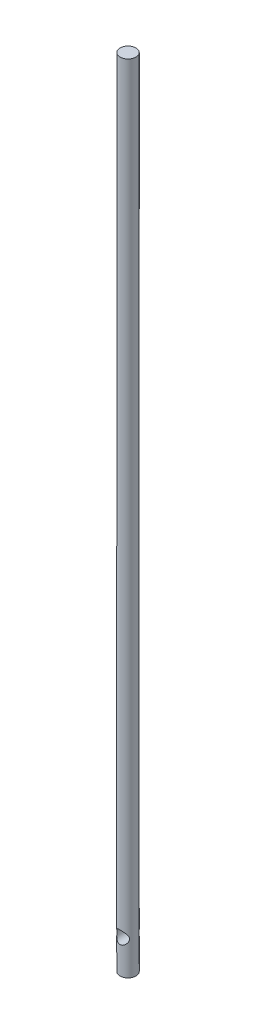
SolidWorks part; units mm, degrees
material "灰铸铁 (SN)"
ref_plane "前视基准面" through (0, 0, 0) normal (0, 0, 1) x (1, 0, 0)
ref_plane "上视基准面" through (0, 0, 0) normal (0, 1, 0) x (1, 0, 0)
ref_plane "右视基准面" through (0, 0, 0) normal (1, 0, 0) x (0, 0, -1)
sketch "草图1" plane through (0, 0, 0) normal (0, 1, 0) x (1, 0, 0)
  circle A0 centre (0, 0) radius 1.5
extrude "凸台-拉伸1" add sketch "草图1" along normal blind 150
sketch "草图3" plane through (0, 0, 0) normal (0, 0, 1) x (1, 0, 0)
  circle A0 centre (0, 6.3386) radius 1.2
  dimension "D1" = 2.4
extrude "切除-拉伸2" cut sketch "草图3" against normal mid plane 300
sketch "草图5" plane through (0, 0, 0) normal (0, 0, 1) x (1, 0, 0)
  line L0 (0, 123.9855) -> (0, 10.9306) construction
  line L1 (1.2, 123.9855) -> (1.2, 10.9306)
  line L2 (-1.2, 123.9855) -> (-1.2, 10.9306)
  arc A0 (1.2, 123.9855) -> (-1.2, 123.9855) centre (0, 123.9855) ccw
  arc A1 (-1.2, 10.9306) -> (1.2, 10.9306) centre (0, 10.9306) ccw
  point P3 (0, 67.458)
  dimension "D1" = 2.4
extrude "切除-拉伸3" cut sketch "草图5" against normal blind 10
sketch "草图9" plane through (0, 0, 0) normal (0, 0, -1) x (-1, 0, 0)
  line L0 (0, 9.7306) -> (0, 125.1855)
  arc A0 (-1.2, 10.9306) -> (1.2, 10.9306) centre (0, 10.9306) ccw construction
  arc A1 (1.2, 123.9855) -> (-1.2, 123.9855) centre (0, 123.9855) ccw construction
sketch "草图10" plane through (0, 0, 0) normal (0, 0, -1) x (-1, 0, 0)
  line L0 (0, 9.7306) -> (0.0037, 63.6289)
